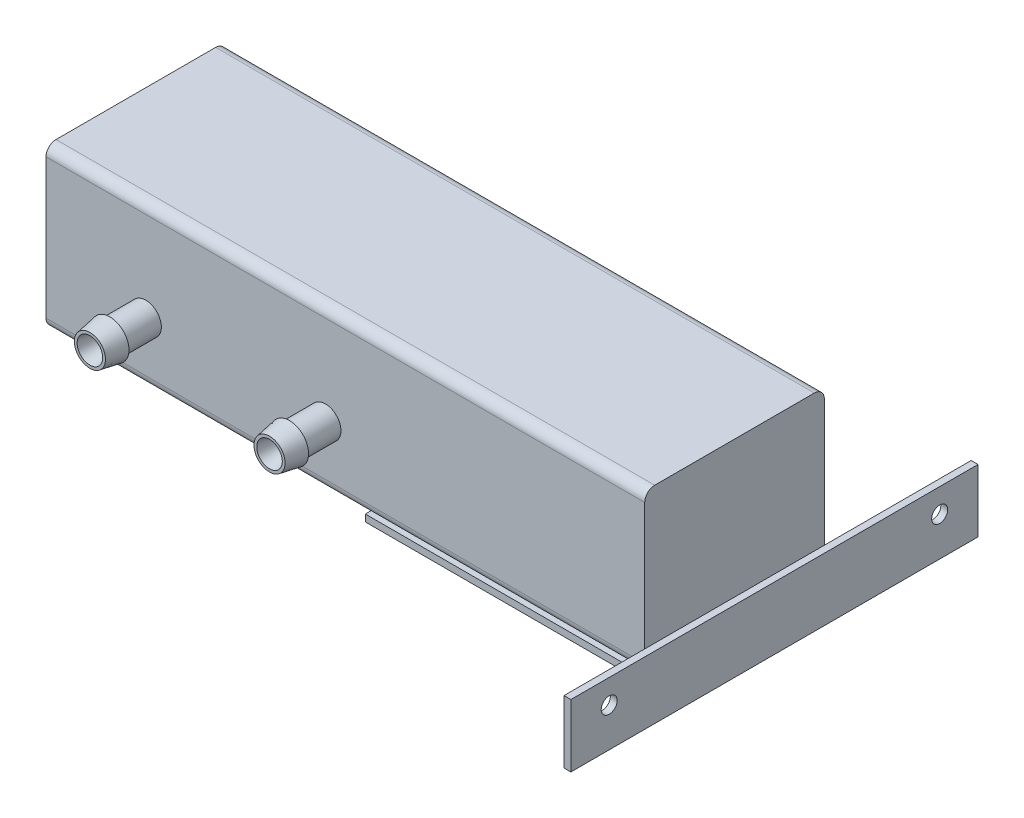
SolidWorks part; units mm, degrees
material "Rubber"
ref_plane "Front" through (0, 0, 0) normal (0, 0, 1) x (1, 0, 0)
ref_plane "Top" through (0, 0, 0) normal (0, 1, 0) x (1, 0, 0)
ref_plane "Right" through (0, 0, 0) normal (1, 0, 0) x (0, 0, -1)
sketch "Sketch1" plane through (0, 0, 0) normal (0, 0, 1) x (1, 0, 0)
  line L0 (52.5, 97.6) -> (52.5, -7.4) construction
  line L1 (-95.25, 25.4) -> (95.25, 25.4)
  line L2 (-95.25, 25.4) -> (-95.25, -25.4)
  line L3 (-95.25, -25.4) -> (95.25, -25.4)
  line L4 (95.25, 25.4) -> (95.25, -25.4)
  line L5 (-95.25, 25.4) -> (95.25, -25.4) construction
  line L6 (-95.25, -25.4) -> (95.25, 25.4) construction
  line L7 (52.5, -7.4) -> (-52.5, -7.4) construction
  line L9 (52.5, 97.6) -> (-52.5, 97.6) construction
  line L11 (-52.5, -7.4) -> (-52.5, 97.6) construction
  line L12 (-52.5, 45.1) -> (-95.25, 45.1) construction
  line L13 (52.5, 45.1) -> (95.25, 45.1) construction
  circle A0 centre (-52.5, 97.6) radius 1.5875 construction
  circle A1 centre (52.5, 97.6) radius 1.5875 construction
  circle A2 centre (52.5, -7.4) radius 1.5875 construction
  circle A3 centre (-52.5, -7.4) radius 1.5875 construction
  point P0 (0, 0)
  point P6 (0, 0)
  dimension "D3" = 3.175
  dimension "D1" = 50.8
  dimension "D2" = 190.5
  dimension "D4" = 105
  dimension "D5" = 105
  dimension "D6" = 18
extrude "Boss-Extrude1" add sketch "Sketch1" along normal mid plane 57.15
sketch "Sketch2" plane through (0, 0, 28.575) normal (0, 0, 1) x (1, 0, 0)
  line L0 (-63.5, -6.35) -> (-6.35, -6.35) construction
  line L1 (-95.25, 25.4) -> (-95.25, -25.4) construction
  line L2 (95.25, 25.4) -> (-95.25, 25.4) construction
  circle A0 centre (-63.5, -6.35) radius 4.953
  circle A1 centre (-6.35, -6.35) radius 4.953
  circle A2 centre (-63.5, -6.35) radius 4.064
  circle A3 centre (-6.35, -6.35) radius 4.064
  dimension "D1" = 9.906
  dimension "D4" = 8.128
  dimension "D2" = 57.15
  dimension "D3" = 31.75
  dimension "D5" = 31.75
  dimension "D6" = 31.75
extrude "Boss-Extrude2" add sketch "Sketch2" along normal blind 17.78
sketch "Sketch3" plane through (0, 0, 46.355) normal (0, 0, 1) x (1, 0, 0)
  circle A0 centre (-63.5, -6.35) radius 4.064 construction
  circle A1 centre (-63.5, -6.35) radius 4.953
  circle A2 centre (-63.5, -6.35) radius 4.953
  circle A3 centre (-6.35, -6.35) radius 4.953
  circle A4 centre (-6.35, -6.35) radius 4.953
  circle A5 centre (-63.5, -6.35) radius 4.064
  circle A6 centre (-6.35, -6.35) radius 4.064 construction
  circle A7 centre (-6.35, -6.35) radius 4.064
  dimension "D1" = 0
  dimension "D2" = 0
extrude "Boss-Extrude3" add sketch "Sketch3" against normal blind 6.35 draft 10 draft outward yes
sketch "Sketch5" plane through (0, 0, 28.575) normal (0, 0, 1) x (1, 0, 0)
  line L0 (-95.25, -25.4) -> (95.25, -25.4) construction
  line L1 (6.35, -25.4) -> (105.7614, -25.4)
  line L2 (6.35, -25.4) -> (6.35, -27.5886)
  line L3 (6.35, -27.5886) -> (107.95, -27.5886)
  line L4 (107.95, -25.4) -> (107.95, -27.5886)
  line L5 (95.25, -25.4) -> (95.25, 25.4) construction
  line L6 (107.95, -25.4) -> (107.95, -7.62)
  line L7 (107.95, -7.62) -> (105.7614, -7.62)
  line L8 (105.7614, -7.62) -> (105.7614, -25.4)
  dimension "D1" = 2.1886
  dimension "D2" = 88.9
  dimension "D3" = 12.7
  dimension "D4" = 17.78
extrude "Boss-Extrude4" add sketch "Sketch5" against normal up to surface (57.15 mm away) separate body up to face at (0, 0, -28.575)
sketch "Sketch7" plane through (0, 0, 0) normal (0, 0, 1) x (1, 0, 0)
  line L1 (107.95, -27.5886) -> (105.7614, -27.5886)
  line L2 (107.95, -27.5886) -> (107.95, -7.62)
  line L3 (107.95, -7.62) -> (105.7614, -7.62)
  line L4 (105.7614, -27.5886) -> (105.7614, -7.62)
extrude "Boss-Extrude5" add sketch "Sketch7" along normal mid plane 129.54
sketch "Sketch8" plane through (105.7614, 0, 0) normal (-1, 0, 0) x (0, 0, 1)
  line L0 (0, 0) -> (0, -15.24) construction
  line L1 (0, -15.24) -> (52.578, -15.24) construction
  line L2 (0, -15.24) -> (-52.578, -15.24) construction
  line L3 (-64.77, -7.62) -> (64.77, -7.62) construction
  circle A0 centre (52.578, -15.24) radius 2.54
  circle A1 centre (-52.578, -15.24) radius 2.54
  dimension "D3" = 5.08
  dimension "D1" = 105.156
  dimension "D2" = 7.62
extrude "Cut-Extrude1" cut sketch "Sketch8" against normal through all
fillet "Fillet1" radius 3.175 4 edges at (0, 25.4, 28.575) (0, 25.4, -28.575) (0, -25.4, -28.575) (0, -25.4, 28.575)
